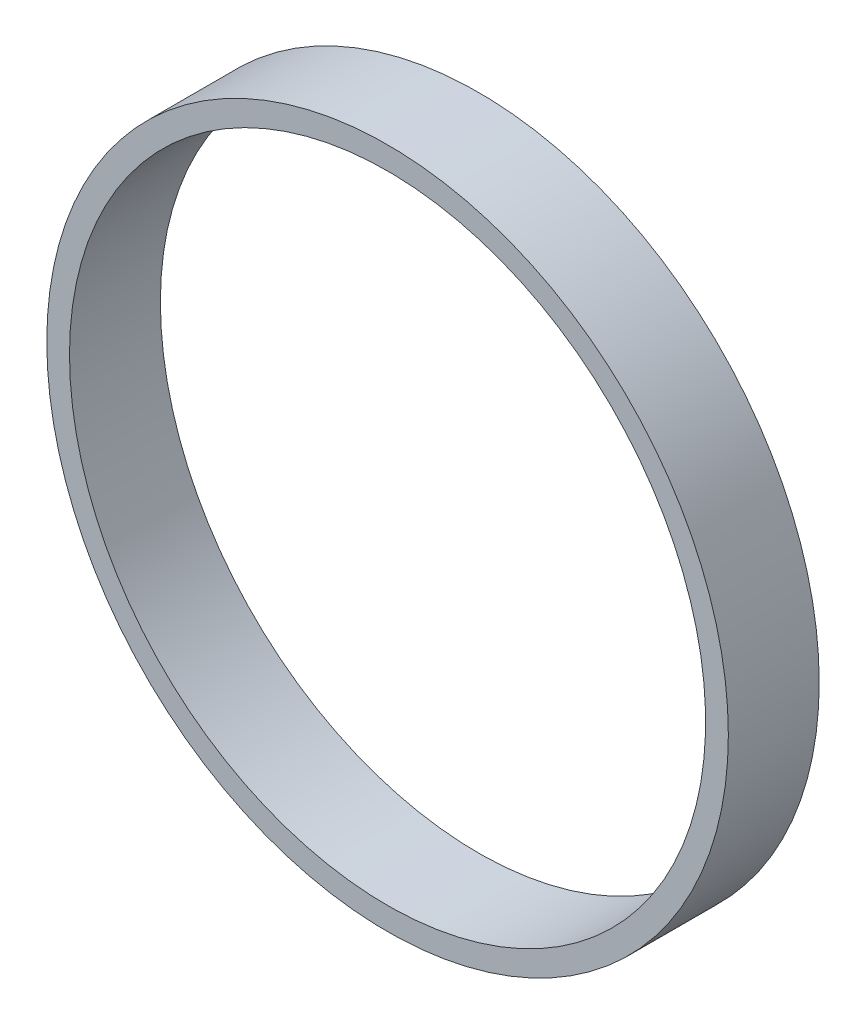
SolidWorks part; units mm, degrees
ref_plane "前视基准面" through (0, 0, 0) normal (0, 0, 1) x (1, 0, 0)
ref_plane "上视基准面" through (0, 0, 0) normal (0, 1, 0) x (1, 0, 0)
ref_plane "右视基准面" through (0, 0, 0) normal (1, 0, 0) x (0, 0, -1)
ref_plane "基准面1" through (0, 0, 0) normal (0, -1, 0) x (1, 0, 0)
sketch "草图1" plane through (0, 0, 0) normal (0, -1, 0) x (1, 0, 0)
  line L0 (22.5, 0) -> (22.5, 6)
  line L1 (22.5, 6) -> (21, 6)
  line L2 (21, 6) -> (21, 0)
  line L3 (21, 0) -> (22.5, 0)
  line L4 (0, 6) -> (0, 0) construction
  dimension "D1" = 21
  dimension "D2" = 22.5
  dimension "D3" = 6
revolve "旋转1" add sketch "草图1" angle 360 about L4
